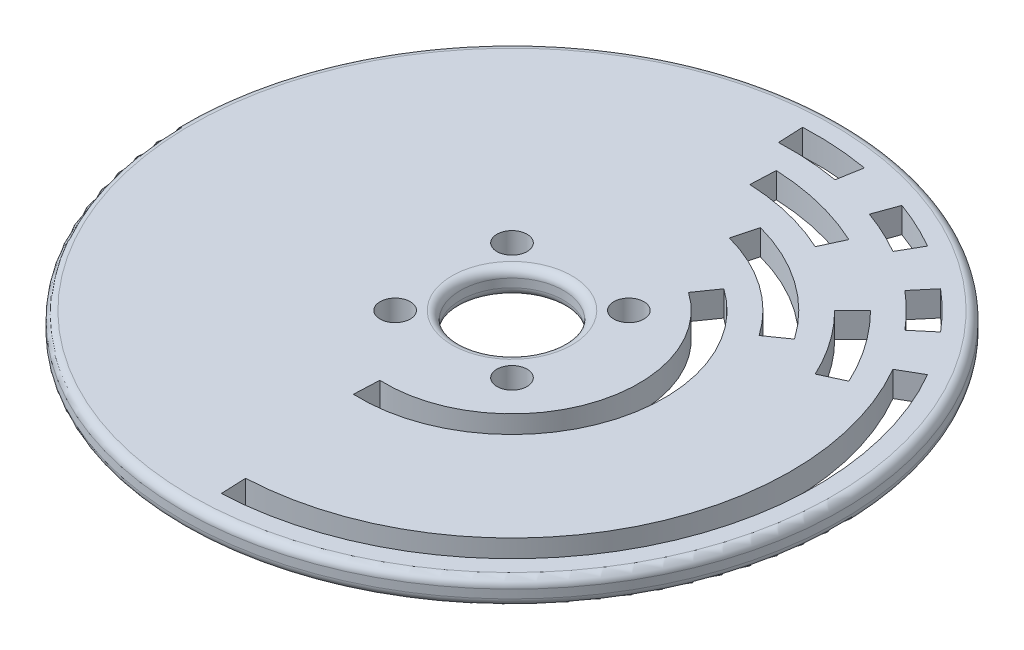
SolidWorks part; units mm, degrees
ref_plane "Front Plane" through (0, 0, 0) normal (0, 0, 1) x (1, 0, 0)
ref_plane "Top Plane" through (0, 0, 0) normal (0, 1, 0) x (1, 0, 0)
ref_plane "Right Plane" through (0, 0, 0) normal (1, 0, 0) x (0, 0, -1)
sketch "Sketch1" plane through (0, 0, 0) normal (0, 1, 0) x (1, 0, 0)
  line L0 (0, 0) -> (8.1776, 8.1776) construction
  circle A0 centre (0, 0) radius 6.096
  circle A1 centre (6.9148, 6.9148) radius 1.7859
  circle A2 centre (6.9148, -6.9148) radius 1.7859
  circle A3 centre (-6.9148, -6.9148) radius 1.7859
  circle A4 centre (-6.9148, 6.9148) radius 1.7859
  point P18 (0, 0)
  dimension "D2" = 3.5719
  dimension "D3" = 4
sketch "Sketch3" plane through (0, 0, 0) normal (0, 1, 0) x (1, 0, 0)
  line L0 (-0.6543, -14.9857) -> (-0.7851, -17.9829)
  line L1 (1.4394, -32.9686) -> (1.5703, -35.9657)
  line L3 (0, 0) -> (8.5951, 48.7453) construction
  line L4 (0, 0) -> (12.8108, 47.8107) construction
  line L5 (0, 0) -> (16.9291, 46.5122) construction
  line L6 (0, 0) -> (20.9185, 44.8598) construction
  line L7 (0, 0) -> (24.7486, 42.8659) construction
  line L8 (0, 0) -> (28.3905, 40.5458) construction
  line L9 (0, 0) -> (31.8162, 37.9171) construction
  line L10 (0, 0) -> (34.9999, 34.9999) construction
  line L11 (0, 0) -> (37.9171, 31.8162) construction
  line L12 (0, 0) -> (40.5458, 28.3905) construction
  line L13 (0, 0) -> (42.8659, 24.7486) construction
  line L14 (-1.5703, 35.9657) -> (-1.4394, 32.9686)
  line L15 (6.2513, 35.4531) -> (5.7304, 32.4987)
  line L16 (12.3127, 33.8289) -> (11.2867, 31.0099)
  line L18 (18, 31.1769) -> (16.5, 28.5788)
  line L19 (23.1404, 27.5776) -> (21.212, 25.2795)
  line L20 (27.5776, 23.1404) -> (25.2795, 21.212)
  line L21 (31.1769, 18) -> (28.5788, 16.5)
  line L22 (0, 0) -> (47.4216, 22.1131) construction
  line L23 (1.3086, 29.9714) -> (1.1777, 26.9743)
  line L24 (12.6785, 27.1892) -> (11.4107, 24.4703)
  line L25 (21.212, 21.2144) -> (19.0908, 19.093)
  line L29 (27.1892, 12.6785) -> (24.4703, 11.4107)
  line L30 (19.6596, 13.7658) -> (17.2022, 12.0451)
  line L31 (6.2117, 23.1822) -> (5.4352, 20.2844)
  line L32 (10.3244, 14.7447) -> (8.6036, 12.2873)
  arc A0 (-0.6543, -14.9857) -> (8.6036, 12.2873) centre (0, 0) ccw
  arc A1 (-0.7851, -17.9829) -> (10.3244, 14.7447) centre (0, 0) ccw
  arc A9 (6.2513, 35.4531) -> (-1.5703, 35.9657) centre (0, 0) ccw
  arc A10 (5.7304, 32.4987) -> (-1.4394, 32.9686) centre (0, 0) ccw
  arc A11 (18, 31.1769) -> (12.3127, 33.8289) centre (0, 0) ccw
  arc A12 (16.5, 28.5788) -> (11.2867, 31.0099) centre (0, 0) ccw
  arc A13 (27.5776, 23.1404) -> (23.1404, 27.5776) centre (0, 0) ccw
  arc A14 (25.2795, 21.212) -> (21.212, 25.2795) centre (0, 0) ccw
  arc A15 (12.6785, 27.1892) -> (1.3086, 29.9714) centre (0, 0) ccw
  arc A16 (11.4107, 24.4703) -> (1.1777, 26.9743) centre (0, 0) ccw
  arc A17 (27.1892, 12.6785) -> (21.212, 21.2144) centre (0, 0) ccw
  arc A18 (24.4703, 11.4107) -> (19.0908, 19.093) centre (0, 0) ccw
  arc A19 (19.6596, 13.7658) -> (6.2117, 23.1822) centre (0, 0) ccw
  arc A20 (17.2022, 12.0451) -> (5.4352, 20.2844) centre (0, 0) ccw
  arc A21 (1.4394, -32.9686) -> (28.5788, 16.5) centre (0, 0) ccw
  arc A22 (1.5703, -35.9657) -> (31.1769, 18) centre (0, 0) ccw
  point P14 (0, 0)
  point P16 (0, 0)
  point P19 (0, 0)
  point P32 (0, 0)
  dimension "D1" = 11
sketch "Sketch4" plane through (0, 0, 0) normal (0, 1, 0) x (1, 0, 0)
  circle A0 centre (0, 0) radius 39
extrude "Boss-Extrude1" add sketch "Sketch4" along normal blind 3
extrude "Cut-Extrude1" cut sketch "Sketch3" along normal blind 3
extrude "Cut-Extrude3" cut sketch "Sketch1" along normal blind 3
fillet "Fillet1" radius 1 4 edges at (0, 0, 6.096) (0, 3, 6.096) (0, 3, 39) (0, 0, 39)
